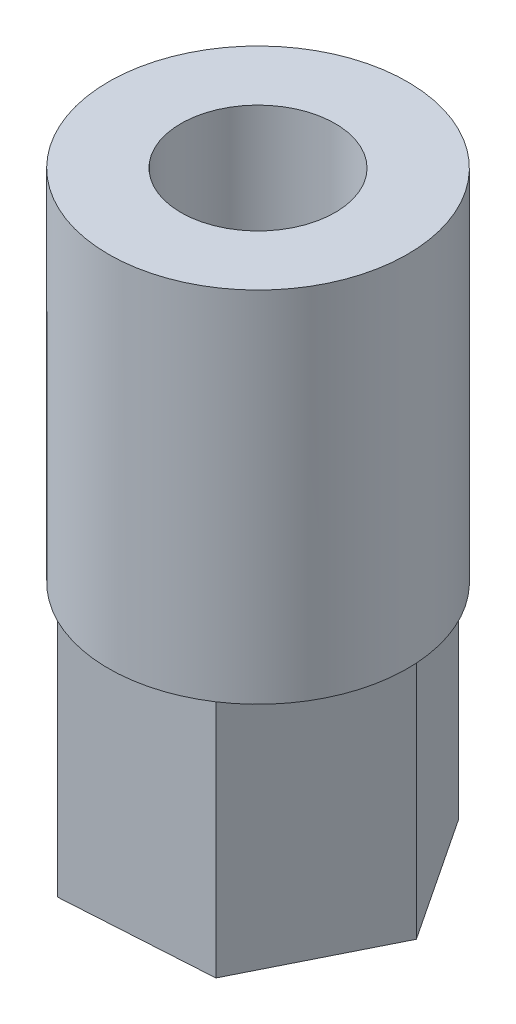
SolidWorks part; units mm, degrees
material "ABS"
ref_plane "Front Plane" through (0, 0, 0) normal (0, 0, 1) x (1, 0, 0)
ref_plane "Top Plane" through (0, 0, 0) normal (0, 1, 0) x (1, 0, 0)
ref_plane "Right Plane" through (0, 0, 0) normal (1, 0, 0) x (0, 0, -1)
sketch "Sketch1" plane through (0, 0, 0) normal (0, 1, 0) x (1, 0, 0)
  circle A0 centre (0, 0) radius 3.175
  dimension "D1" = 6.35
extrude "Boss-Extrude1" add sketch "Sketch1" along normal blind 7.62
sketch "Sketch3" plane through (0, 0, 0) normal (0, -1, 0) x (1, 0, 0)
  line L1 (-1.4167, 2.8414) -> (-3.1691, 0.1938)
  line L2 (-3.1691, 0.1938) -> (-1.7524, -2.6476)
  line L3 (-1.7524, -2.6476) -> (1.4167, -2.8414)
  line L4 (1.4167, -2.8414) -> (3.1691, -0.1938)
  line L5 (3.1691, -0.1938) -> (1.7524, 2.6476)
  line L6 (1.7524, 2.6476) -> (-1.4167, 2.8414)
  circle A0 centre (0, 0) radius 2.7496 construction
extrude "Boss-Extrude2" add sketch "Sketch3" along normal blind 5.08
sketch "Sketch4" plane through (0, 7.62, 0) normal (0, 1, 0) x (1, 0, 0)
  circle A0 centre (0, 0) radius 1.6383
  dimension "D1" = 3.2766
extrude "Cut-Extrude1" cut sketch "Sketch4" against normal blind 8.89
